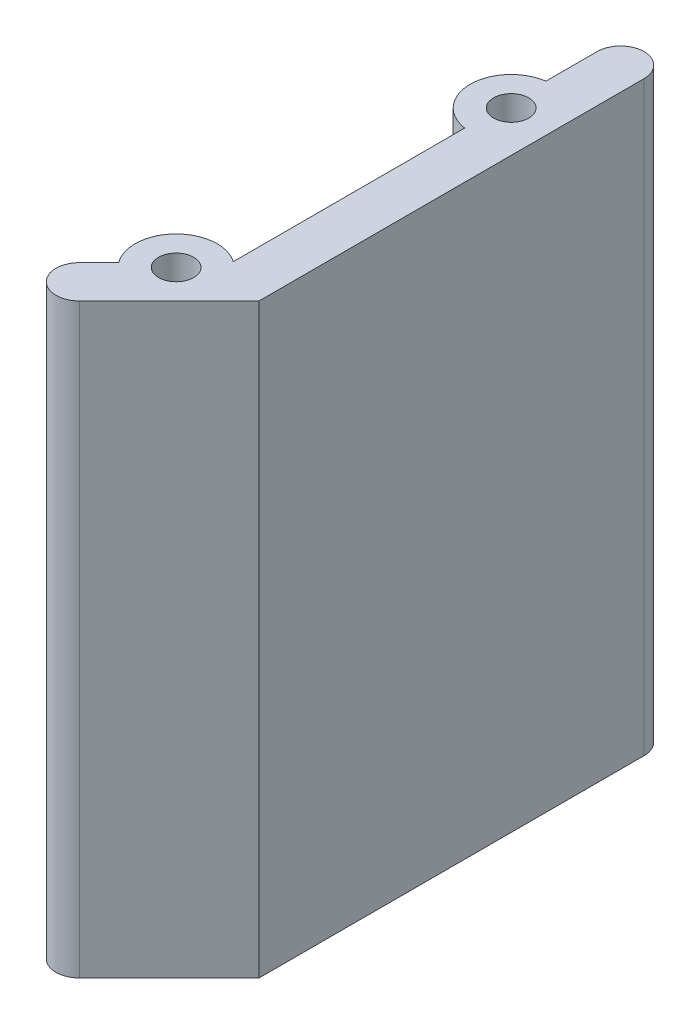
SolidWorks part; units mm, degrees
material "ABS"
ref_plane "Front Plane" through (0, 0, 0) normal (0, 0, 1) x (1, 0, 0)
ref_plane "Top Plane" through (0, 0, 0) normal (0, 1, 0) x (1, 0, 0)
ref_plane "Right Plane" through (0, 0, 0) normal (1, 0, 0) x (0, 0, -1)
sketch "Sketch1" plane through (0, 0, 0) normal (0, 1, 0) x (1, 0, 0)
  line L0 (0, 32) -> (0, 0) construction
  line L1 (0, 0) -> (-7.0711, -7.0711) construction
  line L2 (-2, 32) -> (-2, 0.8284)
  line L3 (-2, 0.8284) -> (-8.4853, -5.6569)
  line L4 (2, 32) -> (2, -0.8284)
  line L5 (2, -0.8284) -> (-5.6569, -8.4853)
  arc A0 (-2, 32) -> (2, 32) centre (0, 32) cw
  arc A1 (-8.4853, -5.6569) -> (-5.6569, -8.4853) centre (-7.0711, -7.0711) ccw
  dimension "D1" = 32
  dimension "D2" = 10
  dimension "D3" = 225
  dimension "D4" = 2
  dimension "D5" = 2
extrude "Boss-Extrude1" add sketch "Sketch1" along normal blind 50
sketch "Sketch5" plane through (0, 0, 0) normal (0, -1, 0) x (-1, 0, 0)
  line L0 (2, 0.8284) -> (8.4853, -5.6569) construction
  line L1 (1.5355, -4.364) -> (-2, -0.8284) construction
  line L2 (4.364, -1.5355) -> (1.5355, -4.364) construction
  line L3 (5.6569, -8.4853) -> (-2, -0.8284) construction
  line L4 (-2, -0.8284) -> (-2, 24.1716) construction
  line L6 (-2, -0.8284) -> (-2, 32) construction
  line L7 (-2, 24.1716) -> (1.5, 24.1716) construction
  circle A0 centre (4.0104, -1.8891) radius 1.5
  circle A1 centre (1.5, 24.1716) radius 1.5
  circle A2 centre (1.5, 24.1716) radius 3.5
  circle A3 centre (4.0104, -1.8891) radius 3.5
  dimension "D1" = 3
  dimension "D2" = 3.5
  dimension "D3" = 5
  dimension "D4" = 25
  dimension "D5" = 3.5
  dimension "D6" = 2
extrude "Boss-Extrude2" add sketch "Sketch5" against normal through all contours A2 | A1 | A3 | A0
sketch "Sketch6" plane through (0, 0, 0) normal (0, -1, 0) x (-1, 0, 0)
  circle A1 centre (4.0104, -1.8891) radius 1.5
  circle A2 centre (1.5, 24.1716) radius 1.5
extrude "Cut-Extrude1" cut sketch "Sketch6" against normal blind 10
sketch "Sketch7" plane through (0, 50, 0) normal (0, 1, 0) x (1, 0, 0)
  circle A0 centre (-4.0104, -1.8891) radius 1.5
  circle A1 centre (-1.5, 24.1716) radius 1.5
extrude "Cut-Extrude2" cut sketch "Sketch7" against normal blind 10
